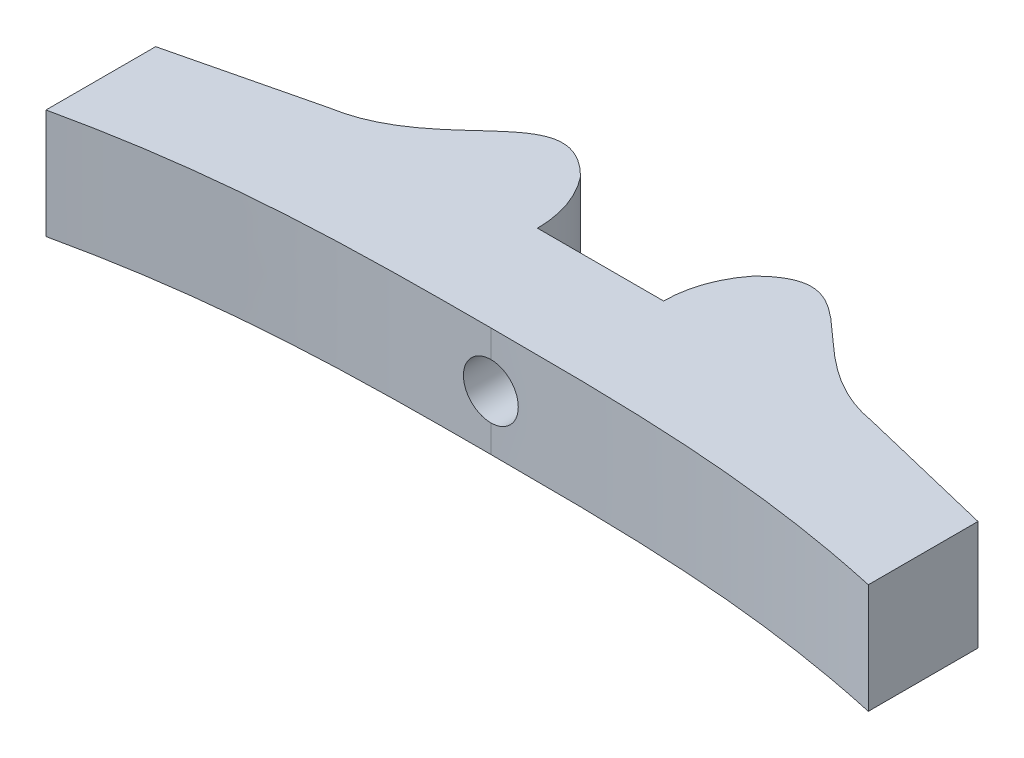
SolidWorks part; units mm, degrees
material "Nylon 101"
ref_plane "Front Plane" through (0, 0, 0) normal (0, 0, 1) x (1, 0, 0)
ref_plane "Top Plane" through (0, 0, 0) normal (0, 1, 0) x (1, 0, 0)
ref_plane "Right Plane" through (0, 0, 0) normal (1, 0, 0) x (0, 0, -1)
sketch "Sketch1" plane through (0, 0, 0) normal (0, 1, 0) x (1, 0, 0)
  line L0 (-2.921, 0) -> (2.921, 0)
  line L1 (0, -8.6636) -> (0, 12.2353) construction
  line L2 (7.7856, -5.08) -> (-7.7856, -5.08) construction
  line L3 (19.05, -6.6418) -> (19.05, -1.5618)
  line L4 (19.05, -1.5618) -> (12.5921, 0)
  line L5 (-19.05, -1.5618) -> (-12.5921, 0)
  line L6 (-19.05, -6.6418) -> (-19.05, -1.5618)
  arc A0 (3.9857, 3.0592) -> (2.921, 0) centre (7.8486, 0) ccw
  arc A1 (-3.9857, 3.0592) -> (-2.921, 0) centre (-7.8486, 0) cw
  spline S0 degree 3 poles (3.9857, 3.0592) (7.0511, 6.1392) (8.0491, 0.7578) (12.5921, 0) knots 0 0 0 0 1 1 1 1
  spline S1 degree 3 poles (-3.9857, 3.0592) (-7.0511, 6.1392) (-8.0491, 0.7578) (-12.5921, 0) knots 0 0 0 0 1 1 1 1
  spline S2 degree 3 poles (0, -5.08) (6.488, -5.08) (12.2109, -5.1333) (19.05, -6.6418) knots 0 0 0 0 1 1 1 1
  spline S3 degree 3 poles (0, -5.08) (-6.488, -5.08) (-12.2109, -5.1333) (-19.05, -6.6418) knots 0 0 0 0 1 1 1 1
  point P7 (0, 0)
  point P17 (0, -6.6418)
  point P19 (0, 0)
  point P23 (0, 0)
  point P24 (19.0756, -6.6418)
  dimension "D1" = 9.8552
  dimension "D2" = 2.921
  dimension "D3" = 5.08
  dimension "D4" = 19.05
  dimension "D5" = 5.08
extrude "Boss-Extrude1" add sketch "Sketch1" along normal blind 5.08
sketch "Sketch2" plane through (0, 0, 0) normal (0, 0, -1) x (-1, 0, 0)
  line L0 (0, 0) -> (0, 5.08) construction
  line L1 (-2.921, 5.08) -> (2.921, 5.08) construction
  circle A0 centre (0, 2.54) radius 1.27
  dimension "D1" = 2.54
extrude "Cut-Extrude1" cut sketch "Sketch2" against normal through all
equation "\"D5@Sketch1\"=\"D3@Sketch1\""
